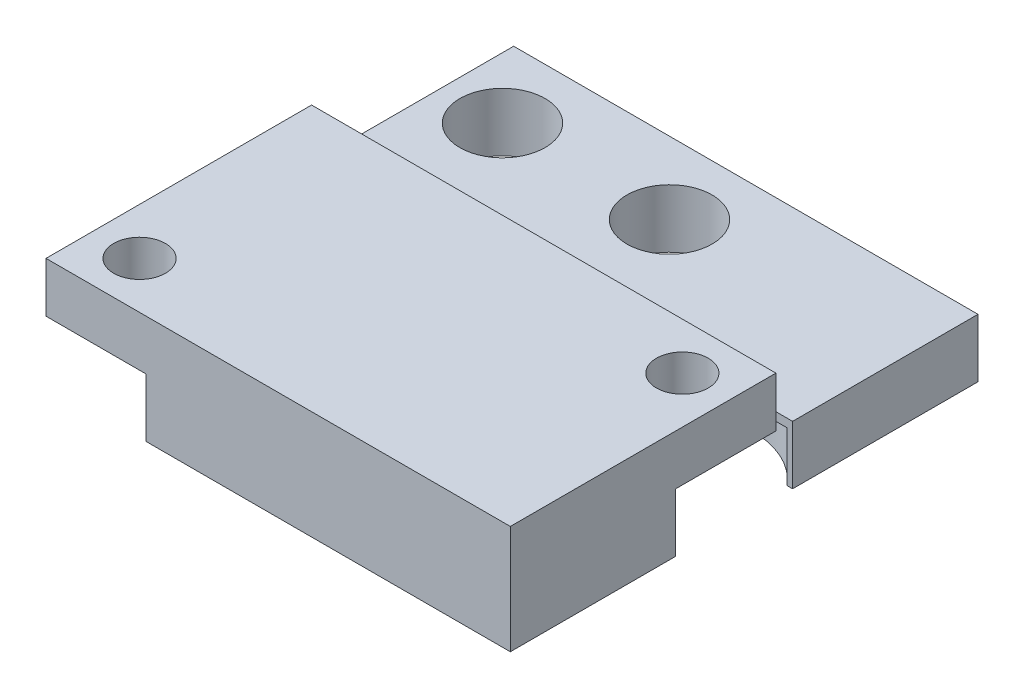
SolidWorks part; units mm, degrees
ref_plane "Front Plane" through (0, 0, 0) normal (0, 0, 1) x (1, 0, 0)
ref_plane "Top Plane" through (0, 0, 0) normal (0, 1, 0) x (1, 0, 0)
ref_plane "Right Plane" through (0, 0, 0) normal (1, 0, 0) x (0, 0, -1)
sketch "Sketch1" plane through (0, 0, 0) normal (0, 1, 0) x (1, 0, 0)
  line L0 (13.65, 23.68) -> (3.65, 23.68) construction
  line L1 (0, 0) -> (27.8, 0)
  line L2 (0, 0) -> (0, 28)
  line L3 (0, 28) -> (27.8, 28)
  line L4 (27.8, 0) -> (27.8, 28)
  circle A0 centre (13.65, 23.68) radius 2.55
  circle A1 centre (3.65, 23.68) radius 2.55
  dimension "D2" = 5.1
  dimension "D1" = 10
  dimension "D3" = 27.8
  dimension "D4" = 28
  dimension "D5" = 23.68
  dimension "D6" = 13.65
extrude "Boss-Extrude1" add sketch "Sketch1" along normal blind 3.5
sketch "Sketch2" plane through (0, 3.5, 0) normal (0, 1, 0) x (1, 0, 0)
  line L0 (27.8, 0) -> (27.8, 28) construction
  line L1 (0, 0) -> (27.8, 0)
  line L2 (0, 0) -> (0, 15.9)
  line L3 (0, 15.9) -> (27.8, 15.9)
  line L4 (27.8, 0) -> (27.8, 15.9)
  circle A0 centre (2.8, 2.8) radius 1.55
  circle A1 centre (25, 13.1) radius 1.55
  dimension "D2" = 3.1
  dimension "D1" = 15.9
  dimension "D3" = 2.8
  dimension "D4" = 2.8
  dimension "D5" = 2.8
  dimension "D6" = 2.8
extrude "Boss-Extrude2" add sketch "Sketch2" along normal blind 3
sketch "Sketch3" plane through (0, 0, 0) normal (0, -1, 0) x (1, 0, 0)
  line L0 (27.8, -28) -> (0, -28)
  line L1 (27.8, -28) -> (0, -28)
  line L2 (0, -28) -> (0, -15.9)
  line L3 (0, -28) -> (0, -15.9)
  line L4 (0, -15.9) -> (0, 0)
  line L6 (0, 0) -> (27.8, 0)
  line L8 (27.8, 0) -> (27.8, -15.9)
  line L10 (27.8, -15.9) -> (27.8, -28)
  line L11 (27.8, -15.9) -> (27.8, -28)
  line L12 (27.8, -28) -> (0, -28)
  line L13 (27.8, -28) -> (0, -28)
  line L14 (0, -28) -> (0, -15.9)
  line L15 (0, -28) -> (0, -15.9)
  line L16 (0, -15.9) -> (0, 0)
  line L17 (0, -15.9) -> (0, 0)
  line L18 (0, 0) -> (27.8, 0)
  line L20 (27.8, 0) -> (27.8, -15.9)
  line L21 (27.8, 0) -> (27.8, -15.9)
  line L22 (27.8, -15.9) -> (27.8, -28)
  line L23 (27.8, -15.9) -> (27.8, -28)
  line L25 (0, 0) -> (6, 0)
  line L26 (0, 0) -> (0, -6)
  line L27 (0, -6) -> (6, -6)
  line L28 (0, 0) -> (0, -15.9)
  line L29 (27.8, 0) -> (0, 0)
  line L30 (27.8, -15.9) -> (27.8, 0)
  line L31 (0, -15.9) -> (27.8, -15.9)
  line L32 (0, 0) -> (0, -15.9)
  line L34 (27.8, -15.9) -> (27.8, 0)
  line L36 (6, 0) -> (6, -6)
  line L37 (27.8, -15.9) -> (22.8, -15.9)
  line L38 (27.8, -15.9) -> (27.8, -10.9)
  line L39 (27.8, -10.9) -> (22.8, -10.9)
  line L40 (22.8, -15.9) -> (22.8, -10.9)
  line M16 (0, 0) -> (0, -28)
  line M19 (27.8, 0) -> (0, 0)
  dimension "D2" = 6
  dimension "D3" = 6
  dimension "D4" = 5
  dimension "D5" = 5
  dimension "D1" = 0
extrude "Cut-Extrude5" cut sketch "Sketch3" against normal blind 3.5 contours L36 L27 M19 M16
sketch "Sketch4" plane through (0, 0, 0) normal (0, -1, 0) x (1, 0, 0)
  line L5 (27.8, 0) -> (27.8, -28) construction
  line L6 (27.8, -16.9) -> (21.8, -16.9)
  line L7 (27.8, -16.9) -> (27.8, -9.9)
  line L8 (27.8, -9.9) -> (21.8, -9.9)
  line L9 (0, 0) -> (0, -15.9)
  line L10 (27.8, 0) -> (0, 0)
  line L11 (27.8, -15.9) -> (27.8, 0)
  line L12 (0, -15.9) -> (27.8, -15.9)
  line L13 (0, 0) -> (0, -15.9)
  line L14 (27.8, 0) -> (0, 0)
  line L15 (27.8, -15.9) -> (27.8, 0)
  line L16 (0, -15.9) -> (27.8, -15.9)
  line L17 (21.8, -16.9) -> (21.8, -9.9)
  line M16 (27.8, -28) -> (27.8, 0)
  dimension "D2" = 6
  dimension "D3" = 7
  dimension "D4" = 1
  dimension "D1" = 0
extrude "Cut-Extrude7" cut sketch "Sketch4" against normal blind 3.5 contours L17 L16 L7 L8 | L17 L6 L16 M16
sketch "Sketch5" plane through (0, 0, 0) normal (0, -1, 0) x (1, 0, 0)
  line L0 (3.65, -23.68) -> (13.65, -23.68) construction
  circle A0 centre (13.65, -23.68) radius 2.55 construction
  circle A1 centre (13.65, -23.68) radius 2.55
  circle A2 centre (23.65, -13.68) radius 5
  point P5 (21.3229, -13.68)
  dimension "D1" = 10
  dimension "D2" = 10
  dimension "D3" = 10
extrude "Cut-Extrude8" cut sketch "Sketch5" against normal blind 3
